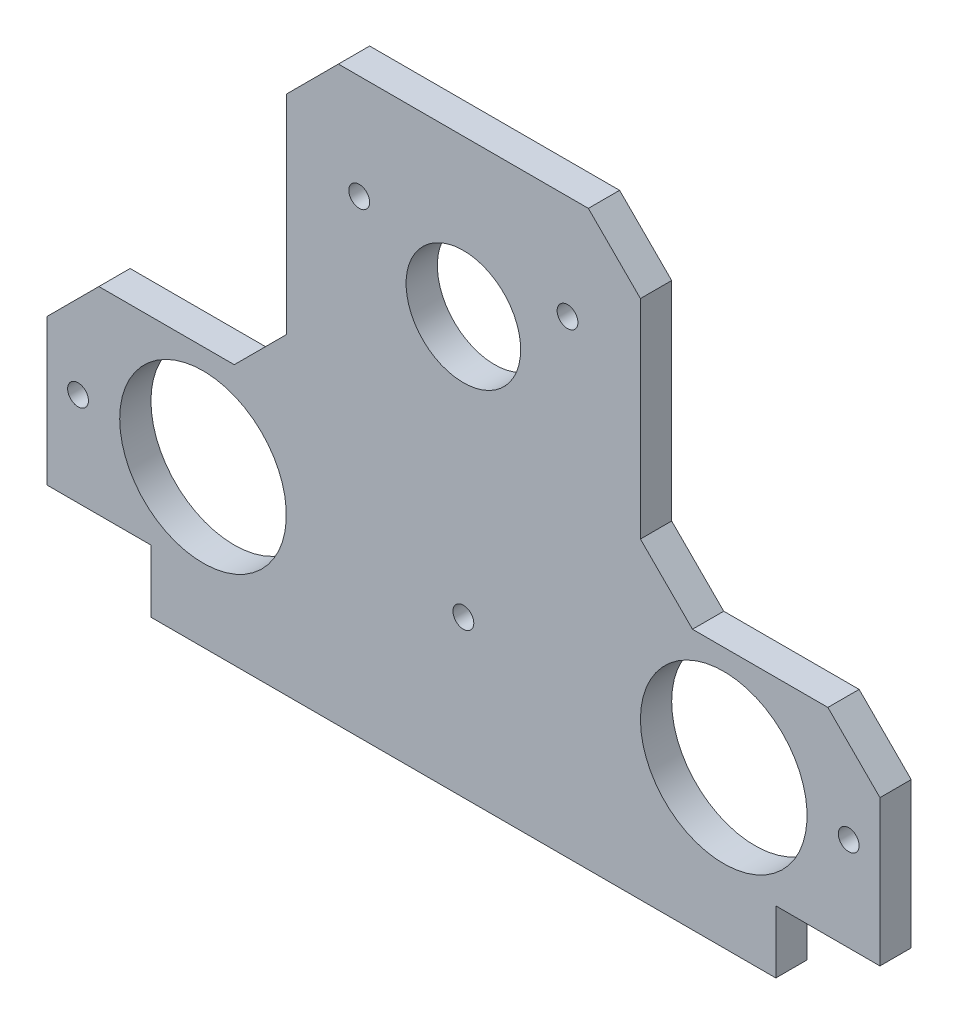
SolidWorks part; units mm, degrees
ref_plane "Plan de face" through (0, 0, 0) normal (0, 0, 1) x (1, 0, 0)
ref_plane "Plan de dessus" through (0, 0, 0) normal (0, 1, 0) x (1, 0, 0)
ref_plane "Plan de droite" through (0, 0, 0) normal (1, 0, 0) x (0, 0, -1)
sketch "Esquisse1" plane through (0, 0, 0) normal (0, 0, 1) x (1, 0, 0)
  line L0 (0, 0) -> (0, 55) construction
  line L1 (-40, 0) -> (40, 0)
  line L2 (40, 0) -> (40, 25)
  line L3 (40, 25) -> (17, 25)
  line L4 (17, 25) -> (17, 55)
  line L5 (17, 55) -> (-17, 55)
  line L6 (-17, 25) -> (-17, 55)
  line L7 (-40, 25) -> (-17, 25)
  line L8 (-40, 0) -> (-40, 25)
  line L9 (17, 40) -> (0, 40) construction
  circle A0 centre (0, 40) radius 13
  dimension "D4" = 26
  dimension "D5" = 40
  dimension "D1" = 80
  dimension "D2" = 34
  dimension "D3" = 30
extrude "Boss.-Extru.1" add sketch "Esquisse1" along normal blind 12
sketch "Esquisse2" plane through (0, 0, 12) normal (0, 0, 1) x (1, 0, 0)
  circle A0 centre (0, 40) radius 13
  circle A1 centre (0, 40) radius 5.5
  dimension "D1" = 26
  dimension "D2" = 11
extrude "Boss.-Extru.2" add sketch "Esquisse2" along normal blind 3 from vertex at -12 starting at point (17, 55, 0)
sketch "Esquisse4" plane through (0, 0, 0) normal (0, 0, -1) x (-1, 0, 0)
  line L0 (0, 0) -> (0, 55) construction
  line L1 (-17, 55) -> (17, 55) construction
  line L3 (40, 0) -> (-40, 0) construction
  line L4 (-40, 0) -> (-40, 25) construction
  circle A0 centre (-25, 15) radius 8
  circle A1 centre (25, 15) radius 8
  dimension "D1" = 16
  dimension "D2" = 15
  dimension "D3" = 15
extrude "Enlèv. mat.-Extru.2" cut sketch "Esquisse4" against normal blind 6
sketch "Esquisse5" plane through (0, 0, 6) normal (0, 0, -1) x (-1, 0, 0)
  line L0 (0, 0) -> (0, 55) construction
  line L1 (40, 0) -> (-40, 0) construction
  line L2 (-17, 55) -> (17, 55) construction
  circle A0 centre (-25, 15) radius 3
  circle A1 centre (25, 15) radius 3
  dimension "D1" = 6
extrude "Enlèv. mat.-Extru.3" cut sketch "Esquisse5" against normal through all
sketch "Esquisse6" plane through (0, 0, 12) normal (0, 0, 1) x (1, 0, 0)
  line L0 (0, 0) -> (0, 7.1495) construction
  line L1 (30, 0) -> (30, 6)
  line L2 (-40, 0) -> (-30, 0)
  line L3 (-40, 0) -> (-40, 6)
  line L4 (-40, 6) -> (-30, 6)
  line L5 (-30, 0) -> (-30, 6)
  line L6 (40, 6) -> (30, 6)
  line L7 (40, 0) -> (40, 6)
  line L8 (40, 0) -> (30, 0)
  dimension "D1" = 6
  dimension "D2" = 10
extrude "Enlèv. mat.-Extru.4" cut sketch "Esquisse6" against normal up to vertex (12 mm away) up to point (40, 0, 0)
chamfer "Chanfrein1" distance 5 angle 45 6 edges at (40, 25, 6) (17, 25, 6) (-17, 25, 6) (-40, 25, 6) (17, 55, 6) (-17, 55, 6)
sketch "Esquisse7" plane through (0, 0, 0) normal (0, 0, -1) x (-1, 0, 0)
  line L0 (0, 0) -> (0, 55) construction
  line L1 (-12, 55) -> (12, 55) construction
  line L2 (0, 15) -> (-37, 15) construction
  line L3 (30, 0) -> (-30, 0) construction
  circle A0 centre (-10, 45) radius 1
  circle A1 centre (10, 45) radius 1
  circle A2 centre (-37, 15) radius 1
  circle A3 centre (37, 15) radius 1
  circle A4 centre (0, 15) radius 1
  dimension "D3" = 2
  dimension "D1" = 10
  dimension "D2" = 10
  dimension "D4" = 15
  dimension "D5" = 37
extrude "Enlèv. mat.-Extru.5" cut sketch "Esquisse7" against normal up to vertex (12 mm away) up to point (-35, 25, 12)
sketch "Esquisse8" plane through (0, 55, 0) normal (0, 1, 0) x (1, 0, 0)
  line L0 (40, 0) -> (40, -12) construction
  line L1 (35, 0) -> (22, 0) construction
  line L7 (-40, -12) -> (40, -12)
  line L8 (-40, -12) -> (-40, -3)
  line L9 (-40, -3) -> (40, -3)
  line L10 (40, -12) -> (40, -3)
  dimension "D1" = 3
extrude "Enlèv. mat.-Extru.6" cut sketch "Esquisse8" against normal through all
